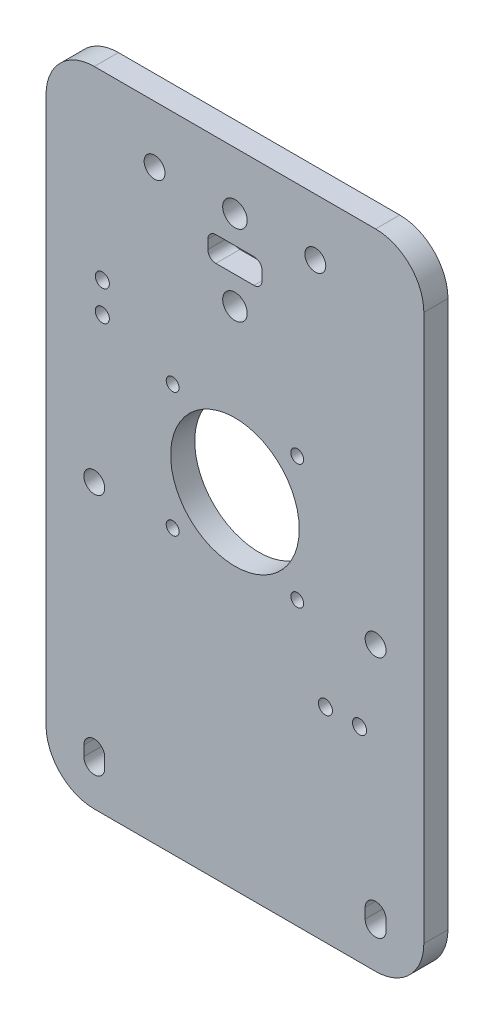
SolidWorks part; units mm, degrees
material "Acrylic (Medium-high impact)"
ref_plane "Спереди" through (0, 0, 0) normal (0, 0, 1) x (1, 0, 0)
ref_plane "Сверху" through (0, 0, 0) normal (0, 1, 0) x (1, 0, 0)
ref_plane "Справа" through (0, 0, 0) normal (1, 0, 0) x (0, 0, -1)
sketch "Model" plane through (0, 0, 0) normal (0, 0, 1) x (1, 0, 0)
  line L0 (-2.3021, 85.8) -> (5.2264, 85.8) construction
  line L1 (6.75, 135.8) -> (-6.75, 135.8) construction
  line L5 (0, 27.6115) -> (0, 21.6925) construction
  line L7 (-15.5, 9.9369) -> (-15.5, 9.0934) construction
  line L8 (15.5, 9.9369) -> (15.5, 9.0934) construction
  line L24 (-35, 37.2847) -> (-35, 77.3985) construction
  line L25 (-31.4983, 12.5) -> (-38.4, 12.5) construction
  line L26 (-31.4983, 10) -> (-38.4, 10) construction
  line L27 (-35, 12.5) -> (-35, 10) construction
  line L28 (-32.4, 12.5) -> (-32.4, 10)
  line L29 (-37.6, 12.5) -> (-37.6, 10)
  line L40 (31.4983, 10) -> (38.4, 10) construction
  line L41 (31.4983, 12.5) -> (38.4, 12.5) construction
  line L42 (35, 37.2847) -> (35, 77.3985) construction
  line L43 (35, 12.5) -> (35, 10) construction
  line L44 (32.4, 12.5) -> (32.4, 10)
  line L45 (37.6, 12.5) -> (37.6, 10)
  line L47 (-26.0102, 145.8) -> (26.0946, 145.8) construction
  line L48 (0, 129.408) -> (0, 90.7064) construction
  line L51 (-38.85, 70.45) -> (-29.8907, 70.45) construction
  line L53 (-16.3166, 125.8) -> (17.7871, 125.8) construction
  line L58 (38.85, 70.45) -> (29.8907, 70.45) construction
  line L4875 (-35, 160) -> (35, 160)
  line L4882 (47, 148) -> (47, 12)
  line L4889 (35, 0) -> (-35, 0)
  line L4896 (-47, 12) -> (-47, 148)
  line L5609 (6.75, 138.9) -> (-6.75, 138.9)
  line L5610 (-6.75, 138.9) -> (-6.75, 132.7)
  line L5611 (-6.75, 132.7) -> (6.75, 132.7)
  line L5612 (6.75, 132.7) -> (6.75, 138.9)
  line L6648 (-6.75, 138.9) -> (6.75, 138.9)
  line L6649 (6.75, 138.9) -> (6.75, 132.7)
  line L6650 (6.75, 132.7) -> (-6.75, 132.7)
  line L6651 (-6.75, 132.7) -> (-6.75, 138.9)
  arc A0 (-47, 12) -> (-35, 0) centre (-35, 12) ccw
  arc A1 (35, 0) -> (47, 12) centre (35, 12) ccw
  arc A2 (47, 148) -> (35, 160) centre (35, 148) ccw
  arc A3 (-35, 160) -> (-47, 148) centre (-35, 148) ccw
  circle A4 centre (0, 85.8) radius 16
  arc A13 (-32.4, 12.5) -> (-37.6, 12.5) centre (-35, 12.5) ccw
  arc A14 (-37.6, 10) -> (-32.4, 10) centre (-35, 10) ccw
  arc A19 (32.4, 12.5) -> (37.6, 12.5) centre (35, 12.5) cw
  arc A20 (37.6, 10) -> (32.4, 10) centre (35, 10) cw
  circle A29 centre (0, 145.8) radius 3.05
  circle A30 centre (-20, 145.8) radius 2.6
  circle A31 centre (20, 145.8) radius 2.6
  circle A32 centre (-35, 70.45) radius 2.6
  circle A33 centre (0, 125.8) radius 3.05
  circle A36 centre (35, 70.45) radius 2.6
  point P17 (0, 0)
  point P77 (-35, 11.25)
  point P114 (35, 11.25)
  point P127 (0, 160)
  dimension "D5" = 32
  dimension "D30" = 5.2
  dimension "D33" = 5.2
  dimension "D35" = 6.1
  dimension "D2" = 70
  dimension "D3" = 160
  dimension "D6" = 15.5
  dimension "D15" = 12
  dimension "D16" = 2.5
  dimension "D17" = 10
  dimension "D18" = 5.2
  dimension "D25" = 14.2
  dimension "D34" = 20
  dimension "D41" = 13.5
  dimension "D42" = 6.2
  dimension "D9" = 70
  dimension "D10" = 57.95
  dimension "D12" = 20
  dimension "D13" = 20
  dimension "D11" = 10
  dimension "D7" = 74.2
extrude "Base" add sketch "Model" along normal blind 6
sketch "Sketch1" plane through (0, 0, 6) normal (0, 0, 1) x (1, 0, 0)
  line L1 (-35, 160) -> (35, 160) construction
  line L2 (-47, 12) -> (-47, 148) construction
  circle A0 centre (-33, 115) radius 1.75
  circle A1 centre (-33, 107.5) radius 1.75
  dimension "D1" = 3.5
  dimension "D3" = 7.5
  dimension "D4" = 14
  dimension "D5" = 45
extrude "SensorMount" cut sketch "Sketch1" against normal through all contours A1 | A0
sketch "Sketch2" plane through (0, 0, 6) normal (0, 0, 1) x (1, 0, 0)
  line L0 (35, 0) -> (-35, 0) construction
  line L1 (-47, 12) -> (-47, 148) construction
  circle A0 centre (22.5, 50.76) radius 1.75
  circle A1 centre (31, 50.76) radius 1.75
  dimension "D1" = 3.5
  dimension "D3" = 8.5
  dimension "D4" = 50.76
  dimension "D5" = 69.5
extrude "CableMount" cut sketch "Sketch2" against normal blind 10 contours A0 | A1
fillet "FilletCableSlot" radius 2 4 edges at (6.75, 138.9, 3) (-6.75, 138.9, 3) (-6.75, 132.7, 3) (6.75, 132.7, 3)
hole_wizard "Ø3.2 (3.2) Stepper mount Holes" positions "Sketch6" profile "Sketch7" hole size "Ø3.2" standard "ANSI Metric" end condition through all
sketch "Sketch6" plane through (0, 0, 6) normal (0, 0, 1) x (1, 0, 0)
  line L0 (-50.1491, 85.8) -> (50.1491, 85.8) construction
  line L2 (0, 0) -> (0, 95.4376) construction
  line L3 (35, 0) -> (-35, 0) construction
  circle A0 centre (0, 85.8) radius 16 construction
  point P0 (-15.5, 101.3)
  point P3 (-15.5, 70.3)
  point P6 (15.5, 70.3)
  point P9 (15.5, 101.3)
  point P22 (0, 85.8)
  dimension "D1" = 31
  dimension "D2" = 31
sketch "Sketch7" plane through (-15.5, 101.3, 6) normal (1, 0, 0) x (0, -1, 0)
  line L0 (0, 0) -> (0, 6)
  line L1 (0, 6) -> (1.6, 6)
  line L2 (1.6, 6) -> (1.6, 0)
  line L5 (1.6, 0) -> (0, 0)
  line L11 (0, -6.35) -> (0, 107.95) construction
  dimension "Thru Hole Dia." = 3.2
  dimension "Thru Hole Depth" = 6
equation "\"D11@Model\"=\"D34@Model\"/2"
